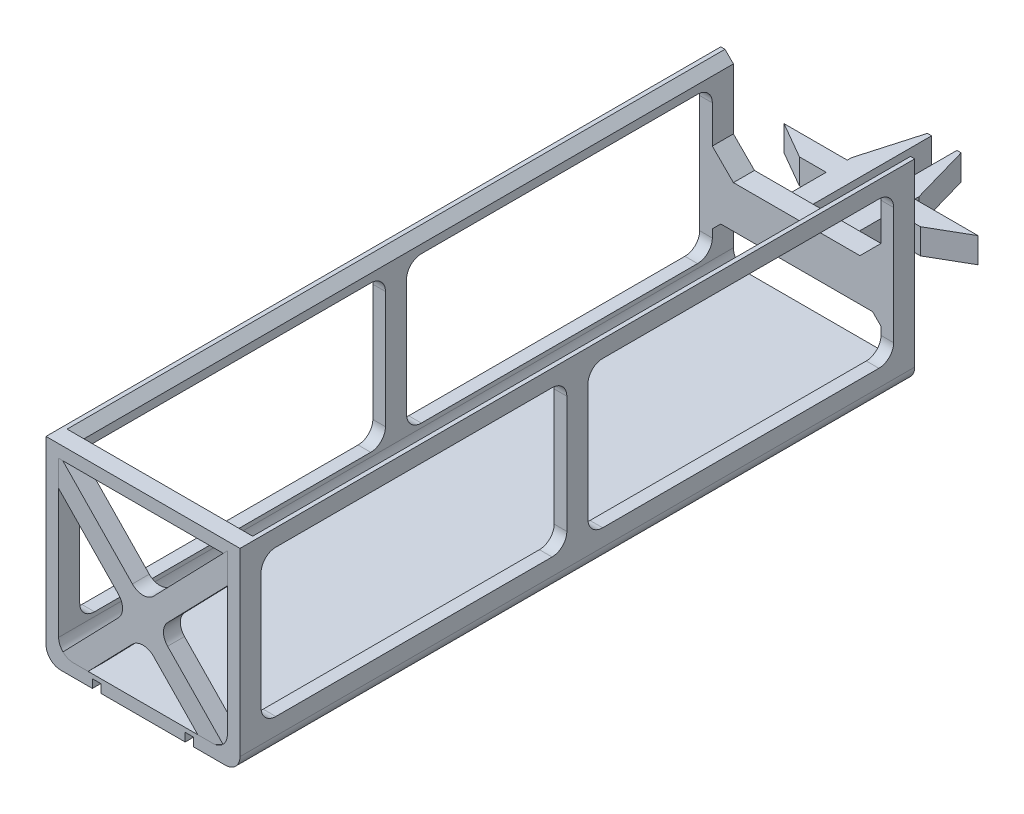
SolidWorks part; units mm, degrees
ref_plane "前视基准面" through (0, 0, 0) normal (0, 0, 1) x (1, 0, 0)
ref_plane "上视基准面" through (0, 0, 0) normal (0, 1, 0) x (1, 0, 0)
ref_plane "右视基准面" through (0, 0, 0) normal (1, 0, 0) x (0, 0, -1)
other "Configuration Table"
sketch "草图1" plane through (0, 0, 0) normal (0, 0, 1) x (1, 0, 0)
  line L0 (0, 43.2634) -> (-3, 43.2634)
  line L1 (3.5, 0) -> (36.5, 0)
  line L2 (0, 3.5) -> (0, 43.2634)
  line L4 (40, 3.5) -> (40, 43.2634)
  line L6 (-3, 43.2634) -> (-3, 0.5)
  line L7 (0.5, -3) -> (39.5, -3)
  line L8 (43, 43.2634) -> (43, 0.5)
  line L9 (40, 43.2634) -> (43, 43.2634)
  arc A4 (36.5, 0) -> (40, 3.5) centre (36.5, 3.5) ccw
  arc A5 (39.5, -3) -> (43, 0.5) centre (39.5, 0.5) ccw
  arc A6 (-3, 0.5) -> (0.5, -3) centre (0.5, 0.5) ccw
  arc A7 (3.5, 0) -> (0, 3.5) centre (3.5, 3.5) cw
  point P16 (0, 47)
  point P21 (40, 0)
  point P28 (0, 0)
  dimension "D1" = 47
  dimension "D2" = 40
  dimension "D4" = 3
  dimension "D5" = 3
  dimension "D6" = 3
extrude "凸台-拉伸1" add sketch "草图1" along normal blind 160
sketch "草图2" plane through (-3, 0, 0) normal (-1, 0, 0) x (0, 0, 1)
  line L0 (0, 21.8817) -> (160, 21.8817) construction
  line L1 (0, 43.2634) -> (0, 0.5) construction
  line L2 (160, 43.2634) -> (160, 0.5) construction
  line L3 (80, 0.5) -> (80, 43.2634) construction
  line L4 (160, 0.5) -> (0, 0.5) construction
  line L5 (160, 43.2634) -> (0, 43.2634) construction
  line L7 (8.5, 39.2634) -> (74, 39.2634)
  line L8 (5, 35.7634) -> (5, 8)
  line L9 (8.5, 4.5) -> (74, 4.5)
  line L10 (77.5, 35.7634) -> (77.5, 8)
  line L11 (86, 39.2634) -> (151.5, 39.2634)
  line L12 (82.5, 35.7634) -> (82.5, 8)
  line L13 (86, 4.5) -> (151.5, 4.5)
  line L14 (155, 35.7634) -> (155, 8)
  arc A0 (151.5, 4.5) -> (155, 8) centre (151.5, 8) ccw
  arc A1 (151.5, 39.2634) -> (155, 35.7634) centre (151.5, 35.7634) cw
  arc A2 (86, 39.2634) -> (82.5, 35.7634) centre (86, 35.7634) ccw
  arc A3 (82.5, 8) -> (86, 4.5) centre (86, 8) ccw
  arc A4 (5, 8) -> (8.5, 4.5) centre (8.5, 8) ccw
  arc A5 (74, 4.5) -> (77.5, 8) centre (74, 8) ccw
  arc A6 (74, 39.2634) -> (77.5, 35.7634) centre (74, 35.7634) cw
  arc A7 (8.5, 39.2634) -> (5, 35.7634) centre (8.5, 35.7634) ccw
  dimension "D8" = 3.5
  dimension "D1" = 4
  dimension "D2" = 5
  dimension "D3" = 4
  dimension "D4" = 5
  dimension "D5" = 5
  dimension "D6" = 4
  dimension "D7" = 2.5
extrude "切除-拉伸1" cut sketch "草图2" against normal blind 160
chamfer "倒角1" distance 2 angle 45 2 edges at (40, 43.2634, 80) (0, 43.2634, 80)
sketch "草图3" plane through (0, 0, 160) normal (0, 0, 1) x (1, 0, 0)
  line L0 (0, 41.2634) -> (0.3207, 40.9323)
  line L4 (0, 22.3817) -> (40, 22.3817) construction
  line L9 (42, 43.2634) -> (44.8214, 45.9289) construction
  line L15 (0.3207, 40.9323) -> (0, 41.2634) construction
  line L16 (0, 3.5) -> (0, 41.2634) construction
  line L17 (0.3207, 40.9323) -> (38.9749, 1.0251)
  line L18 (40, 41.2634) -> (1.0251, 1.0251)
  line L19 (20, 0) -> (20, 44.0956) construction
  line L20 (40, 41.2634) -> (40, 3.5) construction
  line L21 (0, 34.0768) -> (33.0069, 0)
  line L22 (36.5, 0) -> (3.5, 0) construction
  line L23 (6.9931, 0) -> (40, 34.0768)
  line L24 (1.0251, 1.0251) -> (2.6212, -0.5209)
  line L25 (2.6212, -0.5209) -> (6.9931, 0)
  line L26 (33.0069, 0) -> (34.6703, -1.3092)
  line L27 (34.6703, -1.3092) -> (38.9749, 1.0251)
  line L28 (0, 41.2634) -> (0, 34.0768)
  line L29 (40, 41.2634) -> (40, 34.0768)
  line L30 (-2, 43.2634) -> (-1.9372, 43.2634)
  line L31 (-2, 43.2634) -> (42, 43.2634)
  line L33 (42, 43.2634) -> (42, 41.2634)
  line L36 (-1.9372, 43.2634) -> (-6.6947, 48.1751) construction
  line L37 (0, 41.2634) -> (42, 41.2634)
  line L38 (-2, 43.2634) -> (-2, 41.2634)
  line L39 (-2, 41.2634) -> (42, 41.2634)
  arc A0 (36.5, 0) -> (40, 3.5) centre (36.5, 3.5) ccw construction
  arc A1 (0, 3.5) -> (3.5, 0) centre (3.5, 3.5) ccw construction
  line M23 (40, 41.2634) -> (40, 3.5)
  arc M24 (40, 3.5) -> (36.5, 0) centre (36.5, 3.5) cw
  line M25 (36.5, 0) -> (3.5, 0)
  arc M26 (3.5, 0) -> (0, 3.5) centre (3.5, 3.5) cw
  line M27 (0, 3.5) -> (0, 41.2634)
  dimension "D1" = 5
  dimension "D2" = 5
extrude "凸台-拉伸3" add sketch "草图3" against normal blind 4 separate body contours L21 L23 L17 L18 | L17 L23 L18 M23 | L27 L17 L23 L21 M24 M25 | L18 L24 L23 L21 M26 M25 | L21 L18 L17 L0 M27
fillet "圆角1" radius 3.5 4 edges at (16.5195, 17.0218, 158) (20, 13.4285, 158) (20, 20.6151, 158) (23.4805, 17.0218, 158)
sketch "草图4" plane through (0, 0, 160) normal (0, 0, 1) x (1, 0, 0)
  line L0 (43, 0.5) -> (43, 43.2634) construction
  line L1 (-3, 43.2634) -> (43, 43.2634)
  line L2 (-3, 43.2634) -> (-3, 40.2634)
  line L3 (-3, 40.2634) -> (43, 40.2634)
  line L4 (43, 43.2634) -> (43, 40.2634)
  dimension "D1" = 3
extrude "凸台-拉伸4" add sketch "草图4" against normal blind 4
sketch "草图5" plane through (0, 0, 0) normal (0, 0, -1) x (-1, 0, 0)
  line L0 (-43, 21.8817) -> (3, 21.8817) construction
  line L3 (-20, 43.2634) -> (-20, -3) construction
  line L4 (-42, 43.2634) -> (2, 43.2634) construction
  line L5 (-0.5, -3) -> (-39.5, -3) construction
  line L6 (-43, 0.5) -> (-43, 43.2634) construction
  line L7 (-43, 21.8817) -> (3, 21.8817)
  line L8 (-43, 21.8817) -> (-43, 11.8817)
  line L9 (-43, 11.8817) -> (3, 11.8817)
  line L10 (3, 21.8817) -> (3, 11.8817)
  line L11 (3, 43.2634) -> (3, 0.5) construction
  line L12 (0, 40.2634) -> (-40, 40.2634) construction
  line L13 (-36.5, 0) -> (-3.5, 0) construction
  line L14 (0, 3.5) -> (0, 41.2634) construction
  dimension "D1" = 18.3817
  dimension "D2" = 10
  dimension "D3" = 11.8817
  dimension "D4" = 14.8817
  dimension "D5" = 46
  dimension "D6" = 20
extrude "凸台-拉伸5" add sketch "草图5" against normal blind 5
chamfer "倒角2" distance 2 angle 45 2 edges at (0, 11.8817, 2.5) (40, 11.8817, 2.5)
ref_plane "基准面1" through (20, 0, 0) normal (1, 0, 0) x (0, 0, -1)
ref_plane "基准面2" through (0, 14, 0) normal (0, 1, 0) x (1, 0, 0)
sketch "草图7" plane through (0, 14, 0) normal (0, 1, 0) x (1, 0, 0)
  line L0 (20, 7.9641) -> (20, -168.0375) construction
  line L1 (43, 15) -> (34.3397, 10)
  line L2 (0, 0) -> (40, 0) construction
  line L3 (23, 0) -> (28, 0)
  line L4 (23, 0) -> (23, 30)
  line L5 (23, 30) -> (24, 30)
  line L6 (28, 0) -> (28, 10)
  line L8 (28, 15) -> (43, 15)
  line L10 (28, 10) -> (34.3397, 10)
  line L12 (24, 30) -> (28, 16)
  line L13 (28, 15) -> (28, 16)
  line L14 (17, 0) -> (17, 30)
  line L15 (17, 30) -> (16, 30)
  line L16 (16, 30) -> (12, 16)
  line L17 (12, 15) -> (12, 16)
  line L18 (12, 15) -> (-3, 15)
  line L19 (-3, 15) -> (5.6603, 10)
  line L20 (12, 10) -> (5.6603, 10)
  line L21 (12, 0) -> (12, 10)
  line L22 (17, 0) -> (12, 0)
  dimension "D1" = 30
  dimension "D2" = 10
  dimension "D3" = 3
  dimension "D4" = 5
  dimension "D5" = 1
  dimension "D6" = 30
  dimension "D7" = 1
  dimension "D9" = 5
extrude "凸台-拉伸6" add sketch "草图7" along normal blind 6
chamfer "倒角3" distance 5 angle 45 2 edges at (0, 21.8817, 2.5) (40, 21.8817, 2.5)
sketch "草图8" plane through (0, 0, 0) normal (0, 0, -1) x (-1, 0, 0)
  line L0 (-20, -3) -> (-20, 7.0607) construction
  line L1 (-8, -1) -> (-10, -1)
  line L2 (-10, -3) -> (-10, -1)
  line L3 (-0.5, -3) -> (-39.5, -3) construction
  line L4 (-32, -3) -> (-30, -3)
  line L5 (-32, -3) -> (-32, -1)
  line L6 (-32, -1) -> (-30, -1)
  line L7 (-30, -3) -> (-30, -1)
  line L8 (-8, -3) -> (-10, -3)
  line L9 (-8, -3) -> (-8, -1)
  dimension "D1" = 2
  dimension "D2" = 2
  dimension "D3" = 10
extrude "切除-拉伸2" cut sketch "草图8" against normal through all
